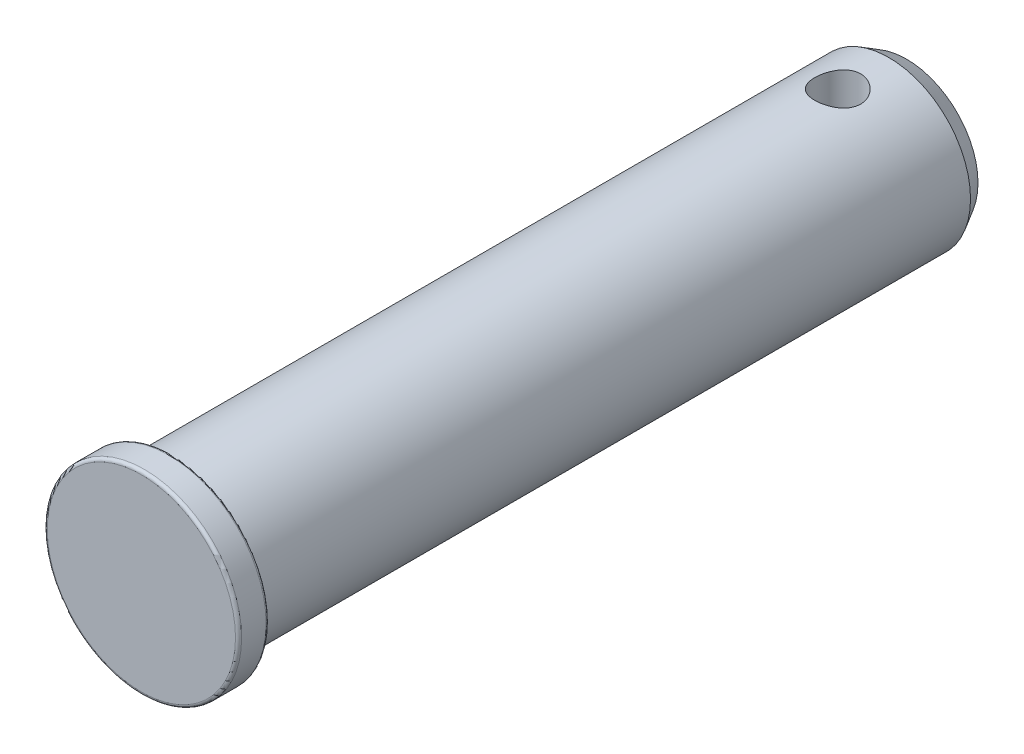
SolidWorks part; units mm, degrees
material "AISI 1045 Acero estirado en frío"
ref_plane "Alzado" through (0, 0, 0) normal (0, 0, 1) x (1, 0, 0)
ref_plane "Planta" through (0, 0, 0) normal (0, 1, 0) x (1, 0, 0)
ref_plane "Vista lateral" through (0, 0, 0) normal (1, 0, 0) x (0, 0, -1)
sketch "Croquis1" plane through (0, 0, 0) normal (1, 0, 0) x (0, 0, -1)
  line L0 (0, 0) -> (75, 0) construction
  line L1 (0, 0) -> (0, 9.525)
  line L2 (3, 8) -> (75, 8)
  line L3 (75, 8) -> (75, 0)
  line L4 (0, 0) -> (75, 0)
  line L6 (0, 9.525) -> (3, 9.525)
  line L7 (3, 9.525) -> (3, 8)
  point P3 (75, 4)
  dimension "D1" = 16
  dimension "D2" = 3
  dimension "D3" = 9.525
  dimension "D4" = 72
revolve "Revolución1" add sketch "Croquis1" angle 360 about L0
sketch "Croquis2" plane through (0, 0, 0) normal (0, 1, 0) x (1, 0, 0)
  line L0 (0, 66) -> (-22.7955, 66) construction
  line L2 (0, 0) -> (0, 70.5) construction
  line L3 (-9.525, 0) -> (9.525, 0) construction
  line L4 (8, 75) -> (-8, 75) construction
  line L5 (8, 75) -> (-8, 75) construction
  circle A0 centre (0, 68.25) radius 2.25
  dimension "D1" = 4.5
  dimension "D2" = 6.75
extrude "Cortar-Extruir1" cut sketch "Croquis2" against normal through all both and the other way through all
fillet "Redondeo1" radius 0.3 1 edges at (8, 0, -3)
chamfer "Chaflán1" distance 1 angle 60 1 edges at (8, 0, -75)
fillet "Redondeo2" radius 0.3 2 edges at (9.525, 0, -3) (9.525, 0, 0)
